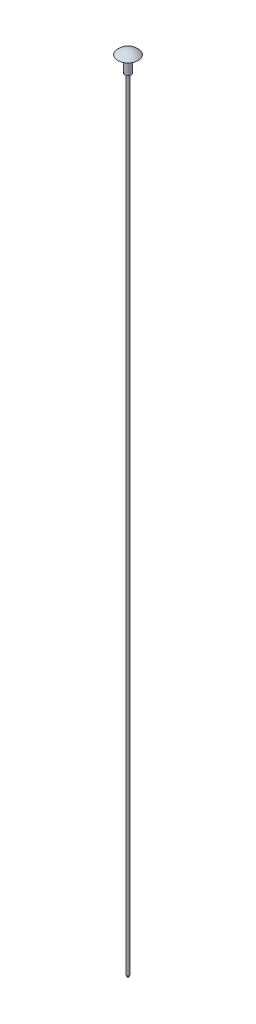
SolidWorks part; units mm, degrees
ref_plane "Front" through (0, 0, 0) normal (0, 0, 1) x (1, 0, 0)
ref_plane "Top" through (0, 0, 0) normal (0, 1, 0) x (1, 0, 0)
ref_plane "Right" through (0, 0, 0) normal (1, 0, 0) x (0, 0, -1)
sketch "Sketch1" plane through (0, 0, 0) normal (0, 0, 1) x (1, 0, 0)
  line L0 (-5, 1300) -> (-5, -1291.3397)
  line L1 (-5, -1291.3397) -> (0, -1300)
  line L2 (0, -1300) -> (0, 1300)
  line L3 (0, 1300) -> (-5, 1300) construction
  line L4 (0, 1300) -> (0, 47.9988) construction
  line L5 (0, -1300) -> (0, -1308.8652) construction
  line L6 (0, 1300) -> (0, 1535.0912) construction
  line L7 (-5, 1300) -> (-10.7784, 1300)
  line L8 (-10.7784, 1300) -> (-10.7784, 1352.8877)
  line L9 (-10.7784, 1352.8877) -> (-33.7761, 1352.8877)
  line L10 (0, 1367.4568) -> (0, 1300)
  arc A0 (-33.7761, 1352.8877) -> (0, 1367.4568) centre (0, 1321.0202) cw
  dimension "D1" = 2600
  dimension "D2" = 30
  dimension "D3" = 10
revolve "Revolve1" add sketch "Sketch1" angle 360 about L6
